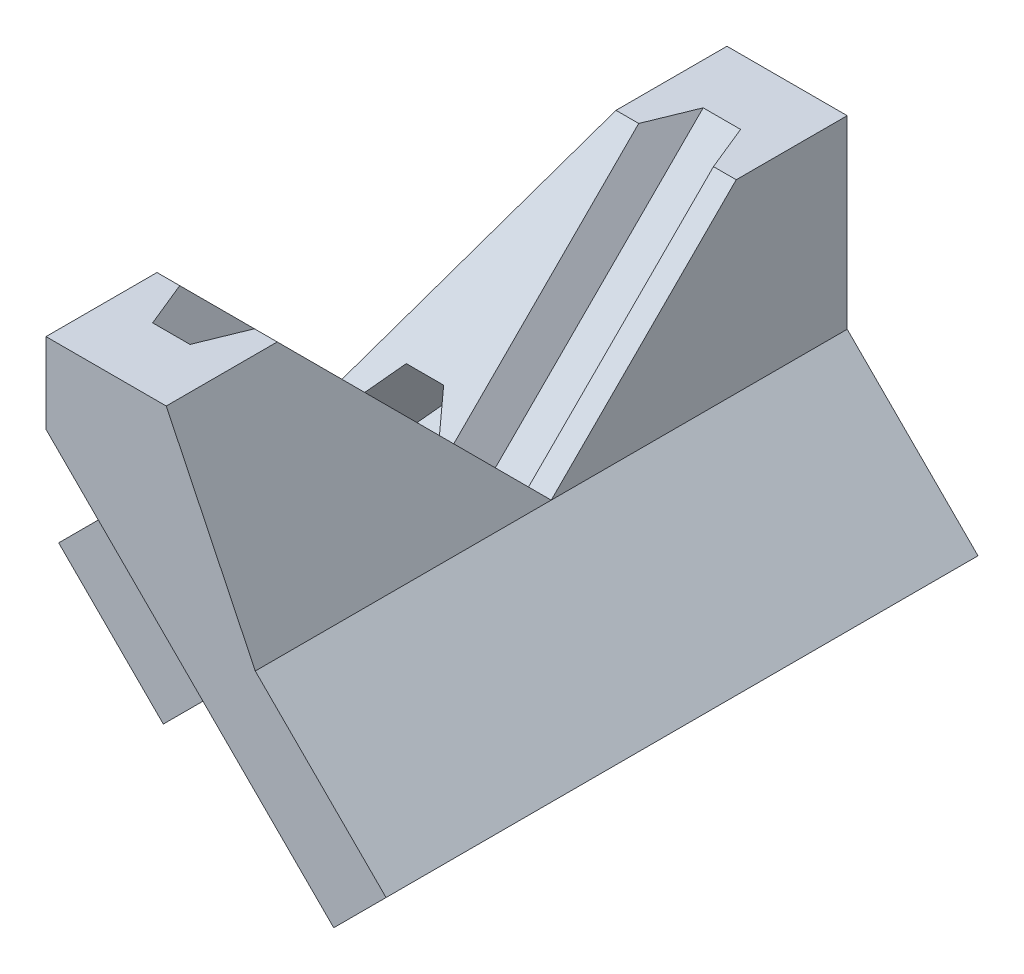
SolidWorks part; units mm, degrees
ref_plane "Front Plane" through (0, 0, 0) normal (0, 0, 1) x (1, 0, 0)
ref_plane "Top Plane" through (0, 0, 0) normal (0, 1, 0) x (1, 0, 0)
ref_plane "Right Plane" through (0, 0, 0) normal (1, 0, 0) x (0, 0, -1)
sketch "Sketch1" plane through (0, 0, 0) normal (0, 0, 1) x (1, 0, 0)
  line L0 (0, 0) -> (5.6569, 5.6569) construction
  line L3 (0, 5.6569) -> (0, 0) construction
  line L4 (0, 0) -> (14.1421, -14.1421)
  line L5 (14.1421, -14.1421) -> (19.799, -8.4853)
  line L6 (19.799, -8.4853) -> (5.6569, 5.6569)
  line L7 (-5.6569, 5.6569) -> (5.6569, 5.6569)
  line L8 (0, 0) -> (-5.6569, 5.6569)
  dimension "D1" = 8
  dimension "D2" = 20
  dimension "D3" = 45
extrude "Boss-Extrude1" add sketch "Sketch1" along normal blind 32
sketch "Sketch2" plane through (0, 0, 0) normal (1, 0, 0) x (0, 0, -1)
  line L0 (-32, 5.6569) -> (0, 5.6569)
  line L2 (-16, 5.6569) -> (-16, 11.3137) construction
  line L3 (-32, 5.6569) -> (-32, 15.6569)
  line L4 (-32, 15.6569) -> (-26, 15.6569)
  line L5 (-26, 15.6569) -> (-16, 5.6569)
  line L6 (-6, 15.6569) -> (-16, 5.6569)
  line L7 (0, 15.6569) -> (-6, 15.6569)
  line L8 (0, 5.6569) -> (0, 15.6569)
  circle A0 centre (-16, 11.3137) radius 4 construction
  dimension "D2" = 90
  dimension "D3" = 8
  dimension "D1" = 10
extrude "Boss-Extrude3" add sketch "Sketch2" along normal up to vertex (5.6569 mm away) and the other way up to vertex (5.6569 mm away) up to point (5.6568, 5.6568, 32)
sketch "Sketch5" plane through (0, 0, 32) normal (0, 0, 1) x (1, 0, 0)
  line L0 (-5.6569, 5.6569) -> (-12.7279, -1.4142)
  line L1 (-12.7279, -1.4142) -> (-4.2426, -9.8995)
  line L2 (-4.2426, -9.8995) -> (-2.1213, -7.7782)
  line L3 (-2.1213, -7.7782) -> (-4.9497, -4.9497)
  line L4 (-4.9497, -4.9497) -> (0, 0)
  line L5 (-5.6569, 5.6569) -> (14.1421, -14.1421) construction
  line L6 (-5.6569, 5.6569) -> (0, 0)
  dimension "D1" = 7
  dimension "D2" = 3
  dimension "D3" = 4
extrude "Boss-Extrude4" add sketch "Sketch5" against normal up to surface (32 mm away) up to face at (5.6569, 3.3333, 0)
sketch "Sketch3" plane through (0, -3.0294, 24.6863) normal (0, 0.7071, 0.7071) x (1, 0, 0)
  line L1 (-1.3965, 14.0343) -> (-3.4172, 14.0343)
  line L2 (-3.4172, 14.0343) -> (-4.4276, 12.2843)
  line L3 (-4.4276, 12.2843) -> (-3.4172, 10.5343)
  line L4 (-3.4172, 10.5343) -> (-1.3965, 10.5343)
  line L5 (-1.3965, 10.5343) -> (-0.3861, 12.2843)
  line L6 (-0.3861, 12.2843) -> (-1.3965, 14.0343)
  line L9 (5.6569, 12.2843) -> (-5.6569, 12.2843) construction
  circle A0 centre (-2.4069, 12.2843) radius 1.75 construction
  dimension "D1" = 3.5
  dimension "D2" = 3.25
extrude "Cut-Extrude1" cut sketch "Sketch3" against normal blind 4 and the other way through all
sketch "Sketch4" plane through (0, -5.1716, 5.1716) normal (0, 0.7071, -0.7071) x (1, 0, 0)
  line L1 (5.6569, -15.3137) -> (-0.3861, -15.3137) construction
  line L2 (4.4276, -15.3137) -> (3.4172, -13.5637)
  line L3 (3.4172, -13.5637) -> (1.3965, -13.5637)
  line L4 (1.3965, -13.5637) -> (0.3861, -15.3137)
  line L5 (0.3861, -15.3137) -> (1.3965, -17.0637)
  line L6 (1.3965, -17.0637) -> (3.4172, -17.0637)
  line L9 (3.4172, -17.0637) -> (4.4276, -15.3137)
  circle A0 centre (2.4069, -15.3137) radius 1.75 construction
  dimension "D1" = 3.25
  dimension "D2" = 3.5
extrude "Cut-Extrude2" cut sketch "Sketch4" against normal blind 4 and the other way through all
sketch "Sketch7" plane through (0, 0, 0) normal (-0.7071, -0.7071, 0) x (0, 0, 1)
  line L0 (32, 0) -> (32, -20) construction
  line L1 (0, -20) -> (12, -20)
  line L2 (0, -20) -> (0, 0)
  line L3 (0, 0) -> (12, 0)
  line L4 (12, -20) -> (12, 0)
  line L6 (16, 0) -> (0, 0) construction
  point P7 (0, 0)
  dimension "D1" = 20
extrude "Cut-Extrude5" cut sketch "Sketch7" against normal through all
sketch "Sketch6" plane through (5.6569, 5.6569, 0) normal (0.7071, 0.7071, 0) x (0, 0, -1)
  line L0 (-32, -20) -> (-32, 0) construction
  line L1 (-22, -10) -> (-32, -10) construction
  line L2 (-22, -10) -> (-22, -20) construction
  line L3 (-32, -20) -> (-12, -20) construction
  circle A0 centre (-22, -10) radius 2.75
  point P4 (-32, -10)
  dimension "D1" = 5.5
extrude "Cut-Extrude3" cut sketch "Sketch6" against normal up to next
sketch "Sketch8" plane through (5.6569, 5.6569, 0) normal (0.7071, 0.7071, 0) x (0, 0, -1)
  circle A0 centre (-22, -10) radius 4.75
  dimension "D1" = 9.5
extrude "Cut-Extrude6" cut sketch "Sketch8" against normal blind 3
sketch "Sketch9" plane through (0, 0, 32) normal (0, 0, 1) x (1, 0, 0)
  line L0 (0.8431, 15.6569) -> (5.6569, 5.6569)
  line L1 (5.6569, 15.6569) -> (-5.6569, 15.6569) construction
  line L2 (5.6569, 5.6569) -> (5.6569, 15.6569)
  line L3 (5.6569, 15.6569) -> (0.8431, 15.6569)
  dimension "D1" = 6.5
extrude "Cut-Extrude7" cut sketch "Sketch9" against normal up to vertex up to point (5.6568, 5.6568, 16)
sketch "Sketch10" plane through (0, 0, 0) normal (0, 0, -1) x (-1, 0, 0)
  line L0 (0.8431, 15.6569) -> (5.6569, 5.6569)
  line L1 (-5.6569, 15.6569) -> (5.6569, 15.6569) construction
  line L2 (5.6569, 5.6569) -> (5.6569, 15.6569)
  line L3 (5.6569, 15.6569) -> (0.8431, 15.6569)
  dimension "D1" = 6.5
extrude "Cut-Extrude8" cut sketch "Sketch10" against normal up to vertex up to point (-5.6568, 5.6568, 16)
sketch "Sketch11" plane through (5.6569, 5.6569, 0) normal (0.7071, 0.7071, 0) x (0, 0, -1)
  line L0 (-12, -16) -> (-16, -20)
  line L1 (-12, -20) -> (-12, 0) construction
  line L2 (-32, -20) -> (-12, -20) construction
  line L3 (-16, -20) -> (-12, -20)
  line L4 (-12, -20) -> (-12, -16)
  dimension "D1" = 4
extrude "Cut-Extrude9" cut sketch "Sketch11" against normal up to next
sketch "Sketch12" plane through (5.6569, 5.6569, 0) normal (0.7071, 0.7071, 0) x (0, 0, -1)
  line L0 (-12, -4) -> (-8, 0)
  line L1 (-12, -16) -> (-12, 0) construction
  line L2 (-12, 0) -> (0, 0) construction
  line L3 (-8, 0) -> (-12, 0)
  line L4 (-12, 0) -> (-12, -4)
  dimension "D1" = 4
extrude "Boss-Extrude5" add sketch "Sketch12" against normal up to surface (8 mm away) up to face at (5.1265, -5.1265, 22)
sketch "Sketch14" plane through (-4.9497, -4.9497, 0) normal (0.7071, 0.7071, 0) x (0, 0, -1)
  line L0 (-8, 0) -> (0, 0)
  line L1 (0, 0) -> (0, -4)
  line L2 (0, -4) -> (-12, -4)
  line L3 (-12, -4) -> (-8, 0)
extrude "Cut-Extrude11" cut sketch "Sketch14" against normal up to next
chamfer "Chamfer7" distance 4 angle 45 1 edges at (-0.7071, -0.7071, 0)
move or copy body "Body-Move/Copy1" bodies to move or copy 116 copy no rotation origin (2.8284, 0, 16) rotation axis (0, 1, 0) rotation angle 180
